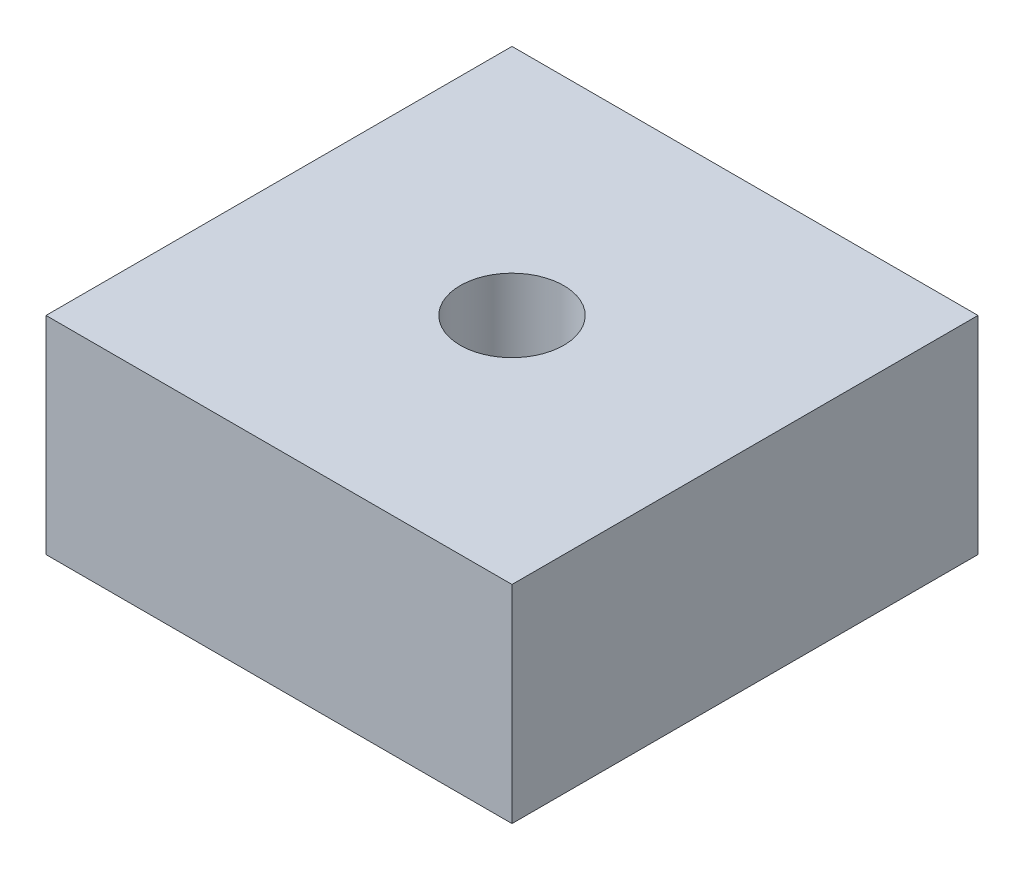
SolidWorks part; units mm, degrees
material "ABS"
ref_plane "Front" through (0, 0, 0) normal (0, 0, 1) x (1, 0, 0)
ref_plane "Top" through (0, 0, 0) normal (0, 1, 0) x (1, 0, 0)
ref_plane "Right" through (0, 0, 0) normal (1, 0, 0) x (0, 0, -1)
sketch "Sketch1" plane through (0, 0, 0) normal (0, 1, 0) x (1, 0, 0)
  line L1 (0, 0) -> (9, 0)
  line L2 (0, 0) -> (0, 9)
  line L3 (0, 9) -> (9, 9)
  line L4 (9, 0) -> (9, 9)
  circle A0 centre (4.5, 4.5) radius 1
  point P7 (0, 0)
  point P8 (4.5, 9)
  point P9 (0, 0)
  point P10 (9, 4.5)
  dimension "D2" = 2
  dimension "D1" = 9
  dimension "D3" = 9
extrude "Boss-Extrude1" add sketch "Sketch1" along normal blind 4
